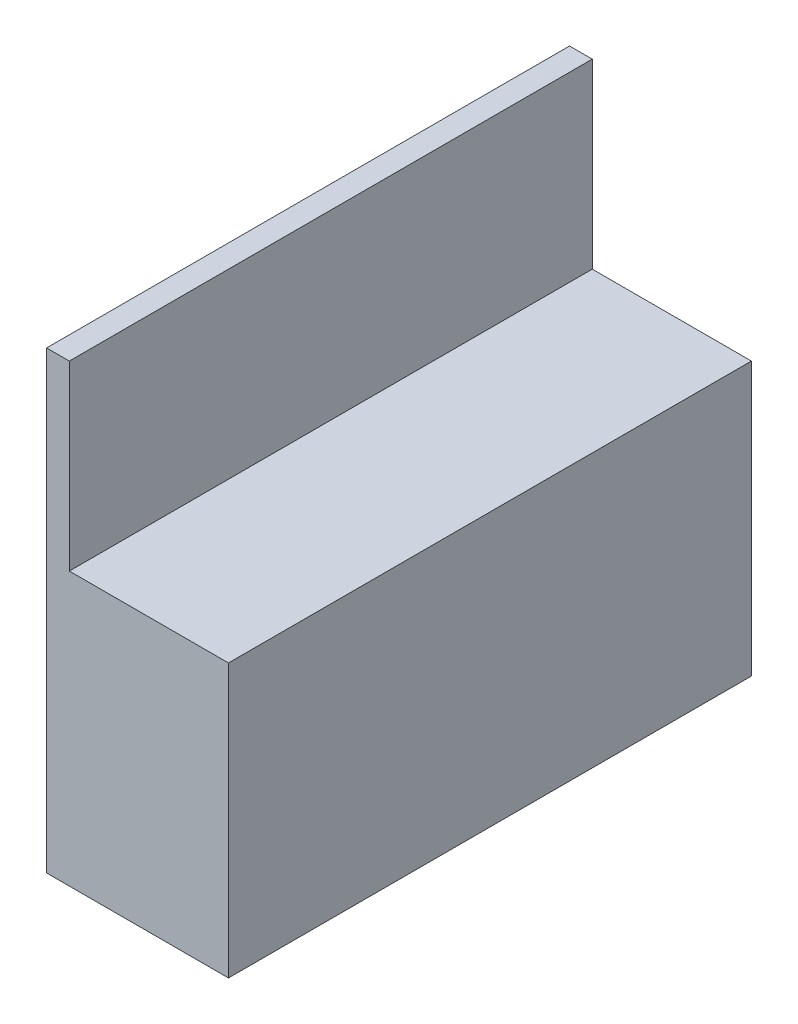
SolidWorks part; units mm, degrees
ref_plane "Front Plane" through (0, 0, 0) normal (0, 0, 1) x (1, 0, 0)
ref_plane "Top Plane" through (0, 0, 0) normal (0, 1, 0) x (1, 0, 0)
ref_plane "Right Plane" through (0, 0, 0) normal (1, 0, 0) x (0, 0, -1)
sketch "Sketch1" plane through (0, 0, 0) normal (0, 0, 1) x (1, 0, 0)
  line L0 (0, 0) -> (0, 40)
  line L1 (0, 40) -> (-5, 40)
  line L2 (-5, 40) -> (-5, -60)
  line L3 (-5, -60) -> (35, -60)
  line L4 (35, -60) -> (35, 0)
  line L5 (0, 0) -> (35, 0)
  point P6 (0, 0)
  dimension "D1" = 5
  dimension "D2" = 40
  dimension "D3" = 100
  dimension "D4" = 35
extrude "Boss-Extrude1" add sketch "Sketch1" along normal blind 115
